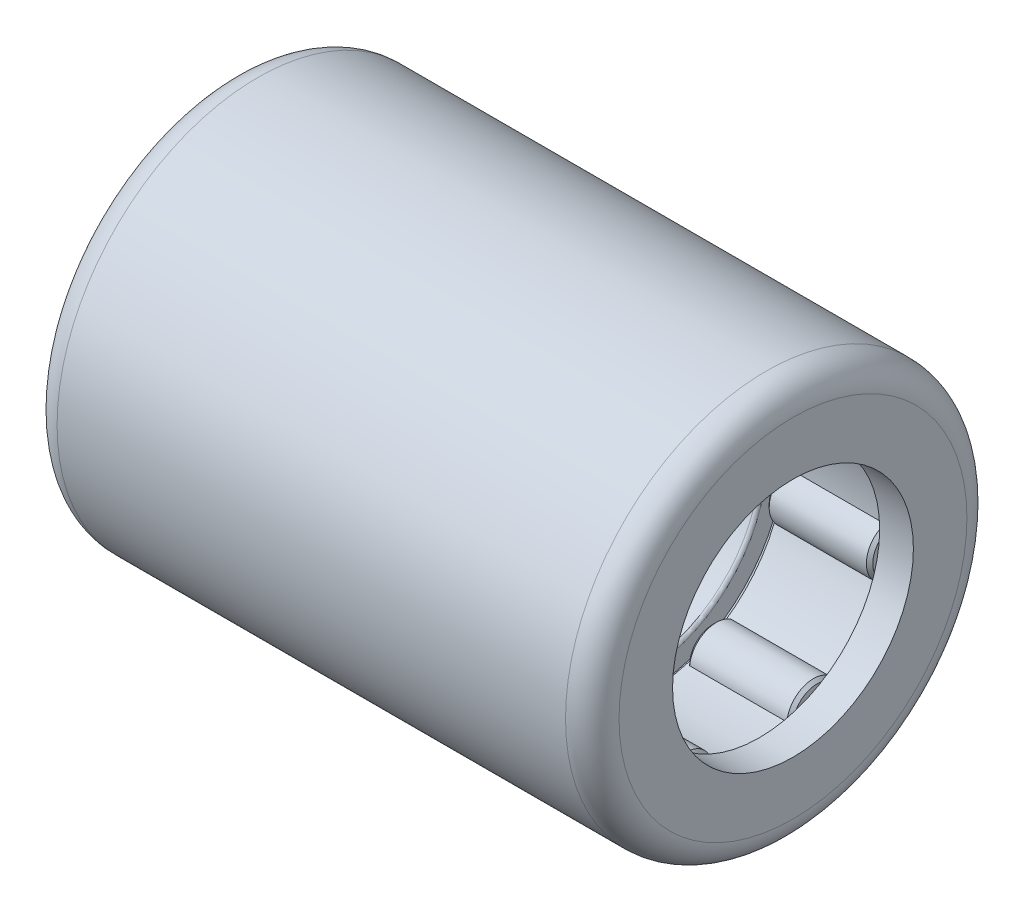
SolidWorks part; units mm, degrees
ref_plane "Front Plane" through (0, 0, 0) normal (0, 0, 1) x (1, 0, 0)
ref_plane "Top Plane" through (0, 0, 0) normal (0, 1, 0) x (1, 0, 0)
ref_plane "Right Plane" through (0, 0, 0) normal (1, 0, 0) x (0, 0, -1)
sketch "Sketch0" plane through (0, 0, 0) normal (0, 0, 1) x (1, 0, 0)
  line L0 (-11.1125, 0) -> (11.1125, 0) construction
  line L1 (-10.0542, 7.9375) -> (10.0542, 7.9375)
  line L2 (-11.1125, 6.8792) -> (-11.1125, 4.7625)
  line L3 (-11.1125, 4.7625) -> (11.1125, 4.7625)
  line L4 (11.1125, 6.8792) -> (11.1125, 4.7625)
  arc A0 (10.0542, 7.9375) -> (11.1125, 6.8792) centre (10.0542, 6.8792) cw
  arc A1 (-10.0542, 7.9375) -> (-11.1125, 6.8792) centre (-10.0542, 6.8792) ccw
  point P11 (-11.1125, 7.9375)
  dimension "D2" = 1.0583
  dimension "Width" = 22.225
  dimension "ID" = 9.525
  dimension "OD" = 15.875
  dimension "D1" = 3.175
sketch "Sketch1" plane through (0, 0, 0) normal (0, 0, 1) x (1, 0, 0)
  line L0 (-11.1125, 6.8792) -> (-11.1125, 4.7625) construction
  line L1 (-10.0542, 7.9375) -> (10.0542, 7.9375) construction
  line L2 (11.1125, 6.8792) -> (11.1125, 4.7625) construction
  line L3 (-11.1125, 6.8792) -> (-11.1125, 4.7625)
  line L4 (-10.0542, 7.9375) -> (10.0542, 7.9375)
  line L5 (11.1125, 6.8792) -> (11.1125, 4.7625)
  line L6 (-11.1125, 4.7625) -> (-9.779, 4.7625)
  line L7 (-11.1125, 4.7625) -> (11.1125, 4.7625) construction
  line L8 (11.1125, 4.7625) -> (9.779, 4.7625)
  line L9 (-5.1744, 4.7625) -> (-4.0409, 4.7625) construction
  line L10 (4.0409, 4.7625) -> (5.1744, 4.7625) construction
  line L11 (5.1744, 4.7625) -> (5.1744, 6.8792) construction
  line L12 (5.1744, 6.8792) -> (9.779, 6.8792)
  line L13 (9.779, 6.8792) -> (9.779, 4.7625)
  line L14 (4.0409, 4.7625) -> (4.0409, 7.3025) construction
  line L15 (4.0409, 7.3025) -> (-4.0409, 7.3025)
  line L16 (-4.0409, 7.3025) -> (-4.0409, 4.7625) construction
  line L17 (-5.1744, 4.7625) -> (-5.1744, 6.8792) construction
  line L18 (-5.1744, 6.8792) -> (-9.779, 6.8792)
  line L19 (-9.779, 6.8792) -> (-9.779, 4.7625)
  line L20 (0, 0) -> (0, 7.3025) construction
  line L21 (-11.1125, 0) -> (11.1125, 0) construction
  line L22 (-5.1744, 6.8792) -> (-4.0409, 7.3025)
  line L23 (4.0409, 7.3025) -> (5.1744, 6.8792)
  arc A0 (-10.0542, 7.9375) -> (-11.1125, 6.8792) centre (-10.0542, 6.8792) ccw construction
  arc A1 (11.1125, 6.8792) -> (10.0542, 7.9375) centre (10.0542, 6.8792) ccw construction
  arc A2 (-10.0542, 7.9375) -> (-11.1125, 6.8792) centre (-10.0542, 6.8792) ccw
  arc A3 (11.1125, 6.8792) -> (10.0542, 7.9375) centre (10.0542, 6.8792) ccw
  dimension "D1" = 1.3335
  dimension "D2" = 8.0818
  dimension "D3" = 1.1335
  dimension "D4" = 2.1167
  dimension "D5" = 2.54
revolve "Revolve1" add sketch "Sketch1" angle 360 about L0
sketch "Sketch2" plane through (0, 0, 0) normal (0, 0, 1) x (1, 0, 0)
  line L0 (-9.779, 5.8208) -> (-5.1744, 5.8208) construction
  line L1 (-9.779, 6.8792) -> (-9.779, 4.7625) construction
  line L2 (-5.1744, 4.7625) -> (-5.1744, 6.8792) construction
  line L3 (-11.1125, 4.7625) -> (11.1125, 4.7625) construction
  line L4 (-9.525, 5.8208) -> (-5.4284, 5.8208)
  line L5 (-9.525, 5.8208) -> (-9.525, 4.8895)
  line L6 (-9.398, 4.7625) -> (-5.5554, 4.7625)
  line L7 (-5.4284, 5.8208) -> (-5.4284, 4.8895)
  line L8 (-9.525, 4.8895) -> (-9.398, 4.7625)
  line L9 (-5.5554, 4.7625) -> (-5.4284, 4.8895)
  line L10 (-7.4767, 5.8208) -> (-7.4767, 0) construction
  line L11 (-11.1125, 0) -> (11.1125, 0) construction
  line L12 (-8.535, 5.8208) -> (-6.4184, 5.8208) construction
  line L13 (-8.535, 5.8208) -> (-7.4767, 0) construction
  line L14 (-7.4767, 0) -> (-6.4184, 5.8208) construction
  point P7 (-5.4284, 4.7625)
  point P8 (-9.525, 4.7625)
  dimension "D1" = 0.254
  dimension "D2" = 0.254
  dimension "D3" = 20.61
revolve "Revolve2" add sketch "Sketch2" angle 360 about L0
mirror "Mirror2" about plane through (0, 0, 0) normal (1, 0, 0) of bodies 102
pattern_circular "CirPattern1" count 7 over 360 about axis through (0, 0, 0) along (1, 0, 0) of bodies 152 102
sketch "Sketch3" plane through (0, 0, 0) normal (0, 0, 1) x (1, 0, 0)
  line L0 (-4.0409, 7.3025) -> (-4.0409, 4.7625) construction
  line L1 (3.5329, 4.3815) -> (3.5329, 6.4982) construction
  line L2 (-3.5329, 5.4398) -> (-3.5329, 4.6355)
  line L3 (-3.2789, 4.3815) -> (3.2789, 4.3815)
  line L4 (3.5329, 5.4398) -> (3.5329, 4.6355)
  line L5 (4.0409, 4.7625) -> (4.0409, 7.3025) construction
  line L6 (-5.1744, 4.7625) -> (-4.0409, 4.7625) construction
  line L7 (-5.1744, 4.7625) -> (-5.1744, 6.8792) construction
  line L8 (-3.5329, 5.4398) -> (3.5329, 5.4398) construction
  line L10 (-3.5329, 4.6355) -> (-3.2789, 4.3815)
  line L11 (3.2789, 4.3815) -> (3.5329, 4.6355)
  line L12 (-3.5329, 5.4398) -> (3.5329, 5.4398)
  line L13 (-1.0583, 5.4398) -> (1.0583, 5.4398) construction
  line L14 (0, 5.4398) -> (0, 0) construction
  line L15 (-1.0583, 5.4398) -> (0, 0) construction
  line L16 (0, 0) -> (1.0583, 5.4398) construction
  point P2 (-3.5329, 4.3815)
  dimension "D1" = 0.508
  dimension "D2" = 0.508
  dimension "D3" = 0.381
  dimension "D4" = 22.019
revolve "Revolve3" add sketch "Sketch3" angle 360 about L12
pattern_circular "CirPattern2" count 11 over 360 about axis through (0, 0, 0) along (1, 0, 0) of bodies 131
sketch "Sketch5" plane through (0, 0, 0) normal (0, 0, 1) x (1, 0, 0)
  line L0 (-5.1744, 4.7625) -> (-4.0409, 4.7625) construction
  line L1 (-5.1744, 4.7625) -> (-5.1744, 6.8792) construction
  line L3 (4.0409, 4.7625) -> (5.1744, 4.7625) construction
  line L5 (4.0409, 4.7625) -> (4.0409, 7.3025) construction
  line L6 (-5.0474, 4.7625) -> (-4.1679, 4.7625)
  line L7 (5.1744, 5.6092) -> (5.1744, 4.8895)
  line L8 (-5.1744, 5.6092) -> (-5.1744, 4.8895)
  line L9 (4.1679, 4.7625) -> (5.0474, 4.7625)
  line L10 (5.1744, 4.7625) -> (5.1744, 6.8792) construction
  line L11 (4.0409, 4.8895) -> (4.0409, 5.0377)
  line L12 (9.779, 6.8792) -> (9.779, 4.7625) construction
  line L13 (-9.779, 6.8792) -> (-5.1744, 6.8792)
  line L14 (-9.779, 6.8792) -> (-9.779, 5.6092)
  line L15 (-9.525, 5.3552) -> (-5.4284, 5.3552)
  line L16 (9.779, 6.8792) -> (9.779, 5.6092)
  line L17 (-4.0409, 7.3025) -> (4.0409, 7.3025)
  line L18 (-9.779, 6.8792) -> (-9.779, 4.7625) construction
  line L19 (5.4284, 5.3552) -> (9.525, 5.3552)
  line L20 (-9.525, 5.8208) -> (-9.525, 4.8895) construction
  line L21 (-3.5329, 5.4398) -> (-3.5329, 4.6355) construction
  line L22 (-4.0409, 5.0377) -> (4.0409, 5.0377)
  line L23 (-9.779, 5.6092) -> (-9.525, 5.3552)
  line L24 (-4.0409, 5.0377) -> (-4.0409, 4.8895)
  line L25 (-5.1744, 6.8792) -> (-4.0409, 7.3025) construction
  line L26 (4.0409, 7.3025) -> (5.1744, 6.8792) construction
  line L27 (-5.1744, 6.8792) -> (-4.0409, 7.3025)
  line L28 (4.0409, 7.3025) -> (5.1744, 6.8792)
  line L29 (5.1744, 6.8792) -> (9.779, 6.8792)
  line L30 (-5.4284, 5.3552) -> (-5.1744, 5.6092)
  line L31 (9.525, 5.3552) -> (9.779, 5.6092)
  line L32 (5.1744, 5.6092) -> (5.4284, 5.3552)
  arc A0 (5.0474, 4.7625) -> (5.1744, 4.8895) centre (5.0474, 4.8895) ccw
  arc A1 (4.1679, 4.7625) -> (4.0409, 4.8895) centre (4.1679, 4.8895) cw
  arc A2 (-4.1679, 4.7625) -> (-4.0409, 4.8895) centre (-4.1679, 4.8895) ccw
  arc A3 (-5.0474, 4.7625) -> (-5.1744, 4.8895) centre (-5.0474, 4.8895) cw
  point P9 (9.779, 5.3552)
  point P10 (-9.779, 5.3552)
  point P15 (-5.1744, 5.3552)
  point P16 (-9.525, 5.3552)
  point P18 (5.1744, 5.3552)
  point P20 (-3.5329, 5.0377)
  dimension "D2" = 0.127
revolve "Revolve4" add sketch "Sketch5" angle 360
equation "\"D2@Sketch0\"=\"D1@Sketch0\"/3."
equation "\"D1@Sketch1\"=\"Width@Sketch0\"*.06"
equation "\"D2@Sketch1\"=\"Width@Sketch0\"/2.750"
equation "\"D3@Sketch1\"=\"D1@Sketch1\"*.85"
equation "\"D4@Sketch1\"=\"D1@Sketch0\"/1.5"
equation "\"D5@Sketch1\"=\"D4@Sketch1\"*1.2"
equation "\"D1@CirPattern1\"=(360/\"D3@Sketch2\")-10"
equation "\"D1@CirPattern2\"=(360/\"D4@Sketch3\")-5"
